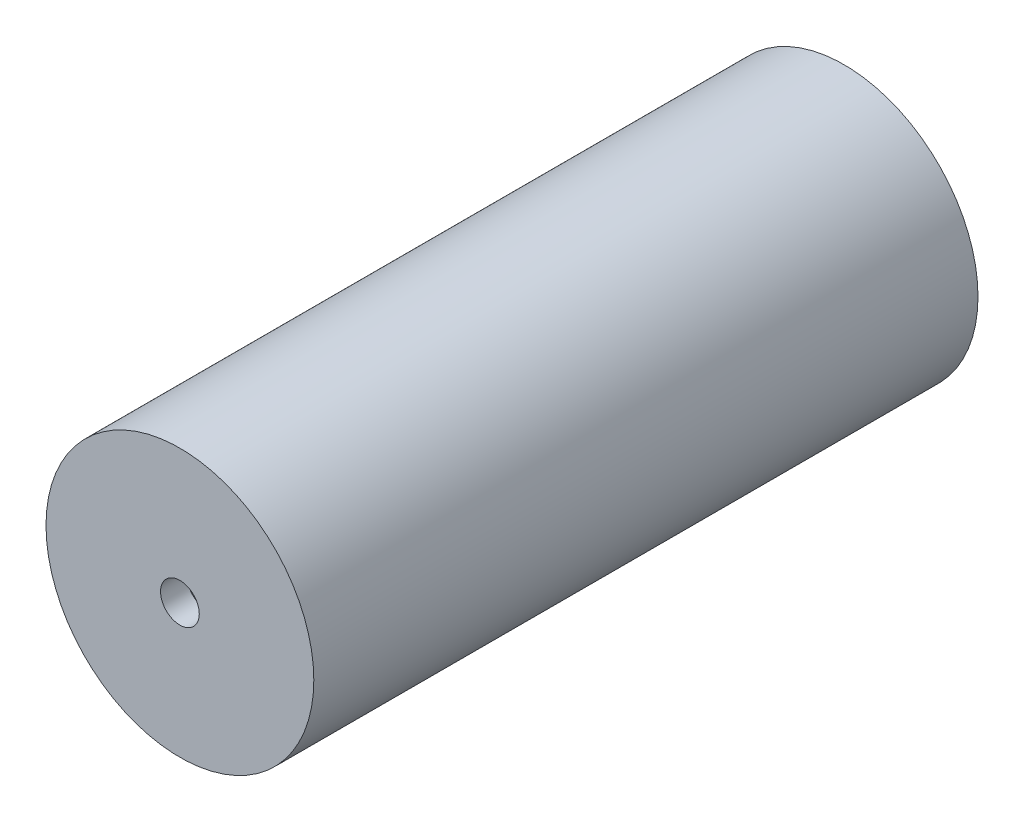
SolidWorks part; units mm, degrees
ref_plane "Front Plane" through (0, 0, 0) normal (0, 0, 1) x (1, 0, 0)
ref_plane "Top Plane" through (0, 0, 0) normal (0, 1, 0) x (1, 0, 0)
ref_plane "Right Plane" through (0, 0, 0) normal (1, 0, 0) x (0, 0, -1)
sketch "Sketch1" plane through (0, 0, 0) normal (0, 0, 1) x (1, 0, 0)
  circle A1 centre (0, 0) radius 252
  dimension "D2" = 504
extrude "Boss-Extrude1" add sketch "Sketch1" along normal blind 50
sketch "Sketch2" plane through (0, 0, 50) normal (0, 0, 1) x (1, 0, 0)
  circle A0 centre (0, 0) radius 202
  circle A1 centre (0, 0) radius 252
  dimension "D1" = 404
extrude "Boss-Extrude2" add sketch "Sketch2" along normal blind 1149.92
sketch "Sketch3" plane through (0, 0, 1199.92) normal (0, 0, 1) x (1, 0, 0)
  circle A0 centre (0, 0) radius 252
extrude "Boss-Extrude3" add sketch "Sketch3" along normal blind 50
sketch "Sketch4" plane through (0, 0, 1249.92) normal (0, 0, 1) x (1, 0, 0)
  circle A0 centre (0, 0) radius 36.45
  dimension "D1" = 72.9
extrude "Cut-Extrude1" cut sketch "Sketch4" against normal through all
sketch "Sketch5" plane through (0, 0, 1249.92) normal (0, 0, 1) x (1, 0, 0)
  line L0 (-252, 0) -> (252, 0) construction
  line L1 (0, -252) -> (0, 252) construction
  circle A0 centre (0, 0) radius 252 construction
sketch "Sketch6" plane through (0, 0, 0) normal (1, 0, 0) x (0, 0, -1)
  line L1 (-1249.92, 0) -> (0, 0) construction
  line L2 (-1249.92, 252) -> (-1249.92, -252) construction
  circle A0 centre (-624.96, 50) radius 11.45
  circle A1 centre (-624.96, -50) radius 11.45
  dimension "D3" = 22.9
  dimension "D4" = 22.9
  dimension "D1" = 50
  dimension "D2" = 50
extrude "Cut-Extrude2" [suppressed] cut sketch "Sketch6" against normal through all
